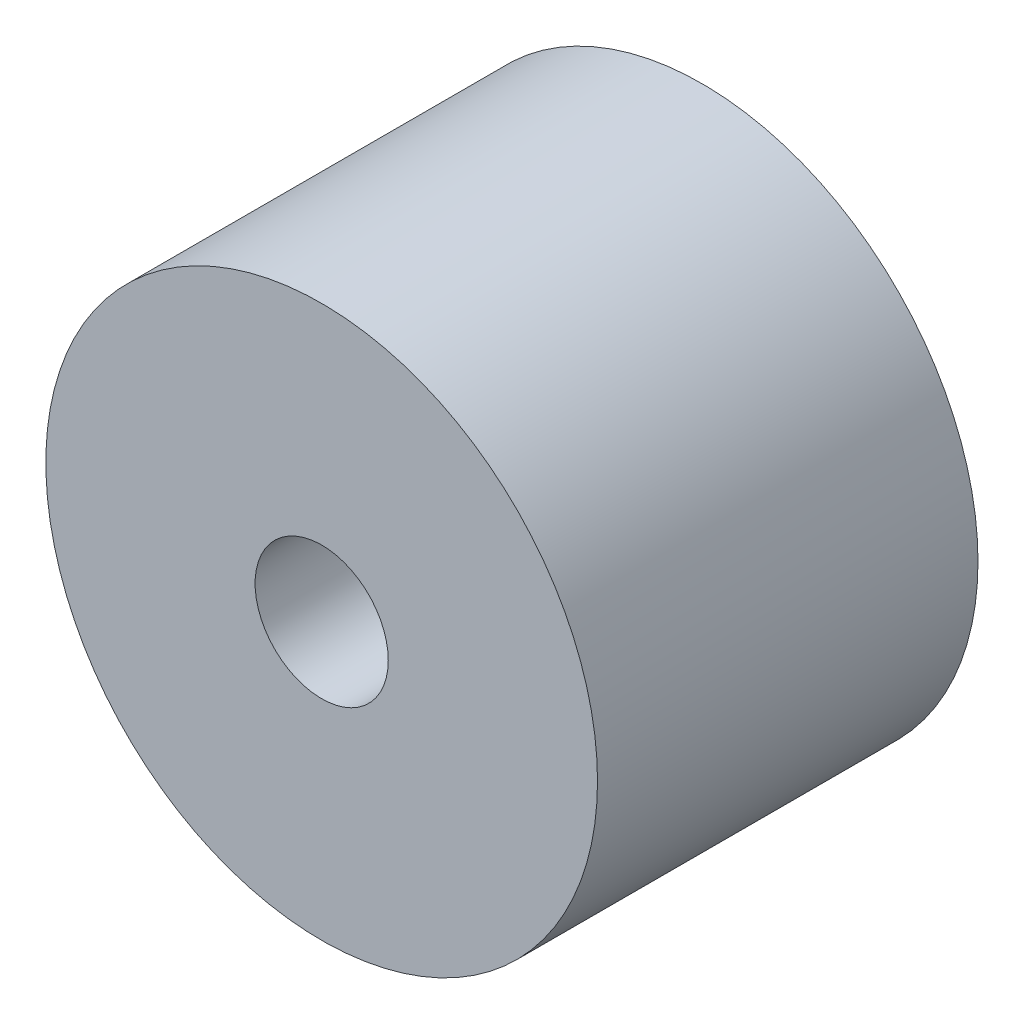
SolidWorks part; units mm, degrees
material "Cobre cromado, UNS C18200"
ref_plane "Front Plane" through (0, 0, 0) normal (0, 0, 1) x (1, 0, 0)
ref_plane "Top Plane" through (0, 0, 0) normal (0, 1, 0) x (1, 0, 0)
ref_plane "Right Plane" through (0, 0, 0) normal (1, 0, 0) x (0, 0, -1)
sketch "Croquis1" plane through (0, 0, 0) normal (0, 0, 1) x (1, 0, 0)
  circle A0 centre (0, 0) radius 3.5
  circle A1 centre (0, 0) radius 14.5
  dimension "D1" = 7
  dimension "D2" = 29
extrude "Saliente-Extruir1" add sketch "Croquis1" along normal blind 20
